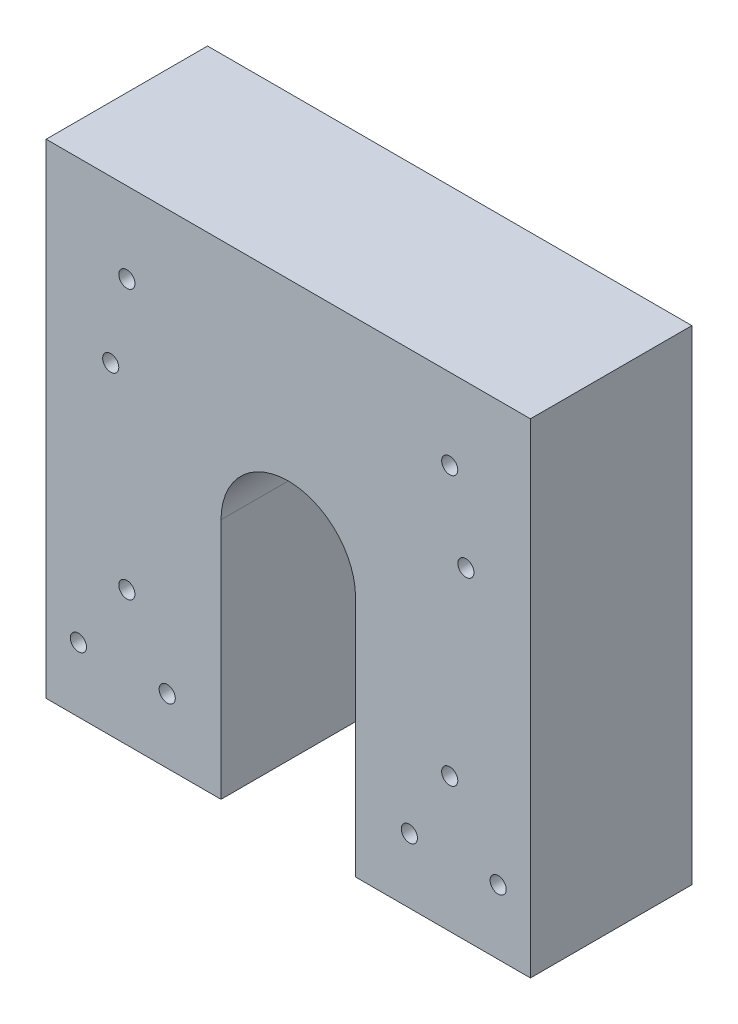
SolidWorks part; units mm, degrees
ref_plane "Front Plane" through (0, 0, 0) normal (0, 0, 1) x (1, 0, 0)
ref_plane "Top Plane" through (0, 0, 0) normal (0, 1, 0) x (1, 0, 0)
ref_plane "Right Plane" through (0, 0, 0) normal (1, 0, 0) x (0, 0, -1)
sketch "Sketch1" plane through (0, 0, 0) normal (0, 0, 1) x (1, 0, 0)
  line L1 (-45, -45) -> (45, -45)
  line L2 (-45, -45) -> (-45, 45)
  line L3 (-45, 45) -> (45, 45)
  line L4 (45, -45) -> (45, 45)
  line L5 (-45, -45) -> (45, 45) construction
  line L6 (-45, 45) -> (45, -45) construction
  point P0 (0, 0)
  dimension "D1" = 90
  dimension "D2" = 90
extrude "Boss-Extrude1" add sketch "Sketch1" along normal blind 30
sketch "Sketch2" plane through (0, -45, 0) normal (0, -1, 0) x (1, 0, 0)
  line L0 (0, 0) -> (0, 30)
  line L1 (-45, 30) -> (45, 30) construction
  circle A1 centre (30, 15) radius 4
  circle A2 centre (-30, 15) radius 4
  dimension "D1" = 30
  dimension "D2" = 30
extrude "Cut-Extrude1" cut sketch "Sketch2" against normal blind 40 contours A2 | A1
sketch "Sketch3" plane through (0, 0, 30) normal (0, 0, 1) x (1, 0, 0)
  line L0 (12.5, 0) -> (12.5, -45)
  line L1 (-45, -45) -> (45, -45) construction
  line L2 (-12.5, 0) -> (-12.5, -45)
  line L3 (-12.5, -45) -> (12.5, -45)
  circle A1 centre (0, 0) radius 12.5
  line M5 (-45, -45) -> (45, -45)
  dimension "D1" = 25
extrude "Cut-Extrude2" cut sketch "Sketch3" against normal blind 35 contours A1 L2 L0 M5 | A1
sketch "Sketch4" plane through (0, 0, 30) normal (0, 0, 1) x (1, 0, 0)
  circle A0 centre (0, 0) radius 20
  circle A1 centre (0, 0) radius 27.5
  dimension "D1" = 55
  dimension "D2" = 40
sketch "Sketch5" plane through (0, 0, 30) normal (0, 0, 1) x (1, 0, 0)
  line L0 (0, 45) -> (0, -45)
  line L1 (45, 45) -> (-45, 45) construction
  line L2 (-45, 45) -> (-45, -45) construction
  line L3 (-12.5, 0) -> (-12.5, -45) construction
  line L4 (-45, -45) -> (-12.5, -45) construction
  line L5 (45, 45) -> (-45, 45) construction
  circle A0 centre (-30, 30) radius 1.5
  circle A1 centre (30, 30) radius 1.5
  circle A2 centre (-22.5, -33) radius 1.5
  circle A3 centre (22.5, -33) radius 1.5
  circle A4 centre (-33, 15) radius 1.5
  circle A5 centre (33, 15) radius 1.5
  circle A6 centre (-39, -33) radius 1.5
  circle A7 centre (39, -33) radius 1.5
  dimension "D1" = 15
  dimension "D3" = 10
  dimension "D2" = 15
  dimension "D4" = 12
  dimension "D5" = 12
  dimension "D6" = 30
  dimension "D7" = 12
  dimension "D8" = 6
extrude "Cut-Extrude3" cut sketch "Sketch5" against normal blind 40 contours A0 | A4 | A1 | A5 | A7 | A3 | A2 | A6
sketch "Sketch9" plane through (0, 0, 30) normal (0, 0, 1) x (1, 0, 0)
  line L0 (-45, 45) -> (-45, -45) construction
  line L1 (-45, -45) -> (-12.5, -45) construction
  line L2 (45, -45) -> (45, 45) construction
  line L3 (12.5, -45) -> (45, -45) construction
  circle A0 centre (-30, -20) radius 1.5
  circle A1 centre (30, -20) radius 1.5
  dimension "D1" = 15
  dimension "D2" = 25
  dimension "D3" = 15
  dimension "D4" = 25
extrude "Cut-Extrude4" cut sketch "Sketch9" against normal blind 15
